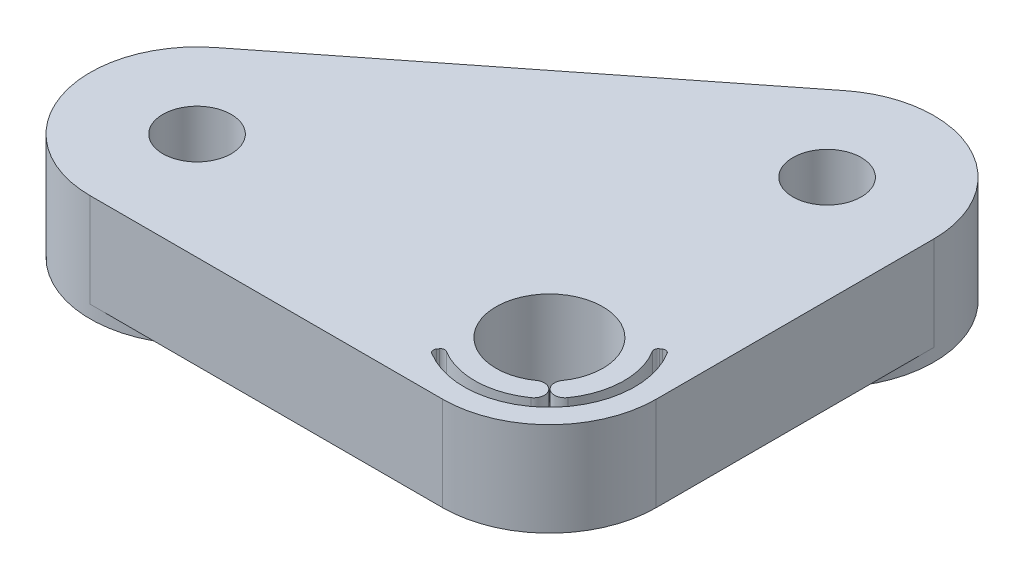
SolidWorks part; units mm, degrees
ref_plane "Front" through (0, 0, 0) normal (0, 0, 1) x (1, 0, 0)
ref_plane "Top" through (0, 0, 0) normal (0, 1, 0) x (1, 0, 0)
ref_plane "Right" through (0, 0, 0) normal (1, 0, 0) x (0, 0, -1)
sketch "Sketch1" plane through (0, 0, 0) normal (0, 1, 0) x (1, 0, 0)
  line L0 (0, 0) -> (16.5, 0) construction
  line L1 (16.5, 0) -> (0, 13) construction
  line L2 (0, 13) -> (0, 0) construction
  line L3 (-5, -5) -> (30.9254, -5)
  line L4 (30.9254, -5) -> (-5, 23.3048)
  line L5 (-5, 23.3048) -> (-5, -5)
  circle A0 centre (16.5, 0) radius 1.6
  circle A1 centre (0, 0) radius 2.5
  circle A2 centre (0, 13) radius 1.6
  dimension "D3" = 5
  dimension "D4" = 3.2
  dimension "D1" = 16.5
  dimension "D2" = 13
  dimension "D5" = 5
extrude "Boss-Extrude1" add sketch "Sketch1" along normal blind 1.57
fillet "Fillet1" radius 5 3 edges at (-5, 0.785, -23.3048) (-5, 0.785, 5) (30.9254, 0.785, 5)
other "Move Face1" [suppressed] parameters "D1"=0.0762
sketch "Sketch2" plane through (0, 1.57, 0) normal (0, 1, 0) x (1, 0, 0)
  line L3 (19.5944, 3.9275) -> (3.0944, 16.9275)
  line L4 (-5, 13) -> (-5, 0)
  line L5 (0, -5) -> (16.5, -5)
  line L6 (19.5944, 3.9275) -> (3.0944, 16.9275)
  line L7 (-5, 13) -> (-5, 0)
  line L8 (0, -5) -> (16.5, -5)
  circle A0 centre (0, 0) radius 2.5 construction
  circle A1 centre (16.5, 0) radius 1.6 construction
  circle A2 centre (0, 13) radius 1.6 construction
  arc A3 (3.0944, 16.9275) -> (-5, 13) centre (0, 13) ccw
  arc A4 (-5, 0) -> (0, -5) centre (0, 0) ccw
  arc A5 (16.5, -5) -> (19.5944, 3.9275) centre (16.5, 0) ccw
  arc A6 (3.0944, 16.9275) -> (-5, 13) centre (0, 13) ccw
  arc A7 (-5, 0) -> (0, -5) centre (0, 0) ccw
  arc A8 (16.5, -5) -> (19.5944, 3.9275) centre (16.5, 0) ccw
  circle A9 centre (0, 0) radius 2.5
  circle A10 centre (16.5, 0) radius 1.6
  circle A11 centre (0, 13) radius 1.6
  dimension "D1" = 0
extrude "Boss-Extrude2" add sketch "Sketch2" along normal blind 2.83
sketch "Sketch3" plane through (0, 0, 0) normal (0, -1, 0) x (1, 0, 0)
  circle A0 centre (16.5, 0) radius 5
  circle A1 centre (0, -13) radius 5
  circle A2 centre (0, -13) radius 1.6 construction
  circle A3 centre (16.5, 0) radius 1.6 construction
  circle A4 centre (0, -13) radius 1.6
  circle A5 centre (16.5, 0) radius 1.6
  arc A6 (19.5944, -3.9275) -> (16.5, 5) centre (16.5, 0) ccw construction
  arc A7 (-5, -13) -> (3.0944, -16.9275) centre (0, -13) ccw construction
extrude "Boss-Extrude3" add sketch "Sketch3" along normal blind 0.6
sketch "Sketch4" plane through (0, 4.4, 0) normal (0, 1, 0) x (1, 0, 0)
  line B0 (2.1191, -3.0264) -> (2.1766, -3.1085)
  line B1 (-3.0264, 2.1191) -> (-3.1085, 2.1766)
  arc B2 (2.1187, -3.3928) -> (-3.3928, 2.1187) centre (0, 0) cw
  arc B3 (-1.4339, -2.0479) -> (-2.0075, -2.867) centre (-1.7207, -2.4575) ccw
  arc B4 (-2.0075, -2.867) -> (1.8496, -2.9714) centre (0, 0) ccw
  arc B5 (-2.867, -2.0075) -> (-2.9714, 1.8496) centre (0, 0) cw
  arc B6 (-2.0479, -1.4339) -> (-2.867, -2.0075) centre (-2.4575, -1.7207) cw
  arc B7 (-1.4339, -2.0479) -> (-2.0479, -1.4339) centre (0, 0) cw
  arc B8 (2.1191, -3.0264) -> (1.8496, -2.9714) centre (1.9553, -3.1411) ccw
  arc B9 (2.1766, -3.1085) -> (2.1187, -3.3928) centre (2.0127, -3.2232) cw
  arc B10 (-3.1085, 2.1766) -> (-3.3928, 2.1187) centre (-3.2232, 2.0127) ccw
  arc B11 (-3.0264, 2.1191) -> (-2.9714, 1.8496) centre (-3.1411, 1.9553) cw
sketch_block_instance "5mm_bore_flexure_relief-1"
sketch_block "5mm_bore_flexure_relief" parameters "D4"=2.5, "D6"=0.2, "D1"=80, "D2"=0.5, "D3"=70, "D5"=1
extrude "Cut-Extrude1" cut sketch "Sketch4" against normal blind 10
mirror "Mirror1" about plane through (-5, 1.57, -23.3048) normal (1, 0, 0) of bodies 106 104
delete or keep bodies "Body-Delete/Keep 1" type keep bodies bodies 105
